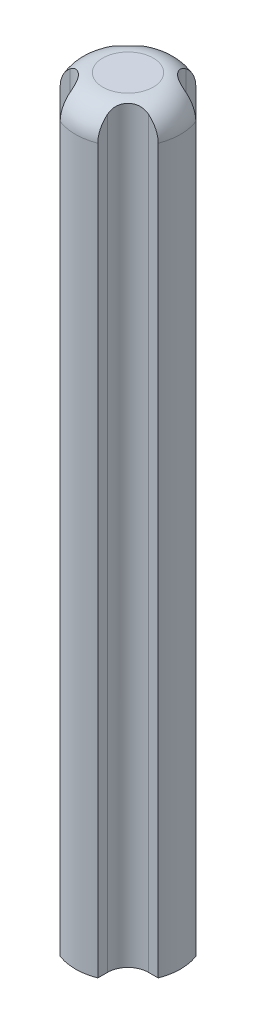
SolidWorks part; units mm, degrees
ref_plane "Front Plane" through (0, 0, 0) normal (0, 0, 1) x (1, 0, 0)
ref_plane "Top Plane" through (0, 0, 0) normal (0, 1, 0) x (1, 0, 0)
ref_plane "Right Plane" through (0, 0, 0) normal (1, 0, 0) x (0, 0, -1)
sketch "Sketch1" plane through (0, 0, 0) normal (0, 1, 0) x (1, 0, 0)
  circle A0 centre (0, 0) radius 3.85
  dimension "D1" = 7.7
extrude "Boss-Extrude1" add sketch "Sketch1" along normal blind 55
fillet "Fillet1" radius 2 1 edges at (0, 55, 3.85)
sketch "Sketch2" plane through (0, 55, 0) normal (0, 1, 0) x (1, 0, 0)
  line L0 (0, 0) -> (1.3789, -1.3789) construction
  line L1 (1.3789, -1.3789) -> (0, -1.3789) construction
  line L2 (1.3789, -1.3789) -> (3.8789, -1.3789)
  line L3 (1.3789, -1.3789) -> (1.3789, -3.8789)
  line L4 (1.3789, -3.8789) -> (3.8789, -3.8789)
  line L5 (3.8789, -1.3789) -> (3.8789, -3.8789)
  line L6 (0, -1.3789) -> (0, 0) construction
  dimension "D1" = 1.95
  dimension "D2" = 2.5
extrude "Cut-Extrude1" cut sketch "Sketch2" against normal through all
pattern_circular "CirPattern1" count 4 over 360 about axis through (0, 0, 0) along (0, 1, 0) of "Cut-Extrude1"
fillet "Fillet2" radius 1.5 4 edges at (1.3789, 27.4987, -1.3789) (-1.3789, 27.4987, -1.3789) (-1.3789, 27.4987, 1.3789) (1.3789, 27.4987, 1.3789)
